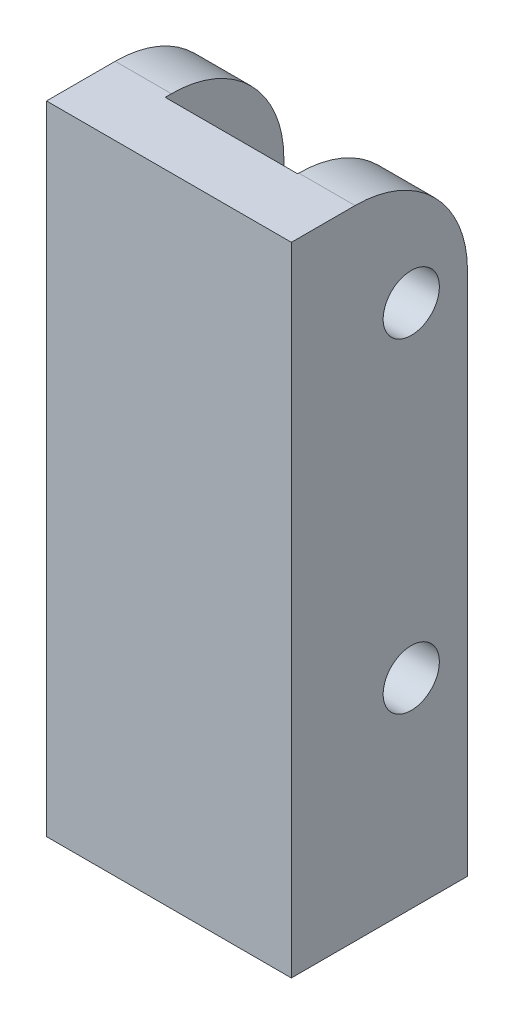
SolidWorks part; units mm, degrees
ref_plane "Спереди" through (0, 0, 0) normal (0, 0, 1) x (1, 0, 0)
ref_plane "Сверху" through (0, 0, 0) normal (0, 1, 0) x (1, 0, 0)
ref_plane "Справа" through (0, 0, 0) normal (1, 0, 0) x (0, 0, -1)
sketch "Эскиз1" plane through (0, 0, 0) normal (0, 1, 0) x (1, 0, 0)
  line L0 (0, 0) -> (10.6, 0)
  line L1 (10.6, 0) -> (10.6, 9.0978)
  line L2 (0, 0) -> (0, 9.5)
  line L3 (0, 9.5) -> (-4.5, 9.5)
  line L4 (-4.5, 9.5) -> (-4.5, -5)
  line L5 (-4.5, -5) -> (15.1, -5)
  line L6 (15.1, -5) -> (15.1, 9.0978)
  line L7 (15.1, 9.0978) -> (10.6, 9.0978)
  dimension "D1" = 10.6
  dimension "D2" = 9.5
  dimension "D3" = 5
  dimension "D4" = 4.5
  dimension "D5" = 4.5
extrude "Бобышка-Вытянуть1" add sketch "Эскиз1" along normal blind 51
sketch "Эскиз2" plane through (15.1, 0, 0) normal (1, 0, 0) x (0, 0, -1)
  line L0 (9.0978, 51) -> (4.5978, 51) construction
  line L1 (-5, 51) -> (9.0978, 51) construction
  line L2 (4.5978, 51) -> (4.5978, 42) construction
  line L3 (4.5978, 42) -> (4.5978, 29) construction
  line L4 (4.5978, 29) -> (4.5978, 16) construction
  circle A0 centre (4.5978, 42) radius 2.25
  circle A1 centre (4.5978, 16) radius 2.25
  dimension "D4" = 4.5
  dimension "D1" = 4.5
  dimension "D2" = 9
  dimension "D3" = 13
extrude "Вырез-Вытянуть1" cut sketch "Эскиз2" against normal through all
fillet "Скругление1" radius 9 2 edges at (-2.25, 51, -9.5) (12.85, 51, -9.0978)
